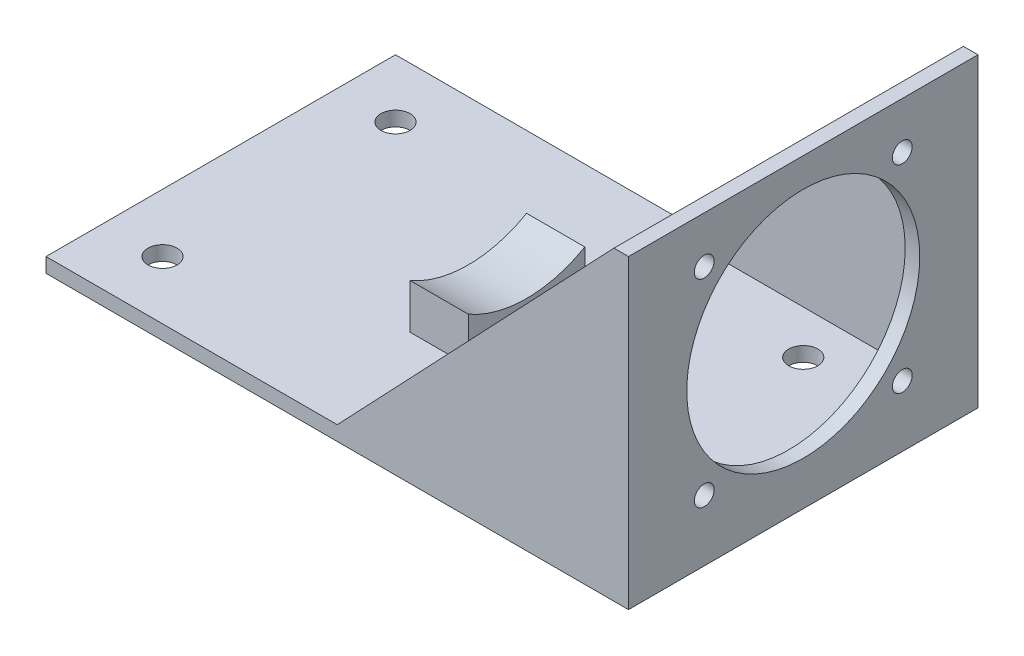
SolidWorks part; units mm, degrees
ref_plane "Front Plane" through (0, 0, 0) normal (0, 0, 1) x (1, 0, 0)
ref_plane "Top Plane" through (0, 0, 0) normal (0, 1, 0) x (1, 0, 0)
ref_plane "Right Plane" through (0, 0, 0) normal (1, 0, 0) x (0, 0, -1)
sketch "Sketch1" plane through (0, 0, 0) normal (0, 1, 0) x (1, 0, 0)
  line L1 (-127, 76.2) -> (127, 76.2)
  line L2 (-127, 76.2) -> (-127, -76.2)
  line L3 (-127, -76.2) -> (127, -76.2)
  line L4 (127, 76.2) -> (127, -76.2)
  line L5 (-127, 76.2) -> (127, -76.2) construction
  line L6 (-127, -76.2) -> (127, 76.2) construction
  point P0 (0, 0)
  dimension "D1" = 254
  dimension "D2" = 152.4
extrude "Boss-Extrude1" add sketch "Sketch1" along normal blind 6.35
sketch "Sketch2" plane through (127, 0, 0) normal (1, 0, 0) x (0, 0, -1)
  line L1 (-76.2, 6.35) -> (76.2, 6.35)
  line L2 (-76.2, 6.35) -> (-76.2, 133.35)
  line L3 (-76.2, 133.35) -> (76.2, 133.35)
  line L4 (76.2, 6.35) -> (76.2, 133.35)
  circle A0 centre (0, 69.85) radius 50.8
  circle A1 centre (-43.18, 26.67) radius 4.318
  circle A2 centre (43.18, 26.67) radius 4.318
  circle A3 centre (43.18, 113.03) radius 4.318
  circle A4 centre (-43.18, 113.03) radius 4.318
  dimension "D5" = 101.6
  dimension "D7" = 8.636
  dimension "D10" = 8.636
  dimension "D12" = 8.636
  dimension "D14" = 8.636
  dimension "D1" = 127
  dimension "D2" = 152.4
  dimension "D3" = 76.2
  dimension "D4" = 63.5
  dimension "D6" = 43.18
  dimension "D8" = 43.18
  dimension "D9" = 43.18
  dimension "D11" = 43.18
  dimension "D13" = 43.18
  dimension "D15" = 43.18
  dimension "D16" = 43.18
  dimension "D17" = 43.18
extrude "Boss-Extrude2" add sketch "Sketch2" against normal blind 6.35
sketch "Sketch3" plane through (0, 0, 76.2) normal (0, 0, 1) x (1, 0, 0)
  line L0 (120.65, 133.35) -> (0, 6.35)
  line L1 (-127, 6.35) -> (120.65, 6.35) construction
  line L2 (0, 6.35) -> (120.65, 6.35)
  line L3 (120.65, 6.35) -> (120.65, 133.35)
extrude "Boss-Extrude3" add sketch "Sketch3" against normal blind 6.35
sketch "Sketch4" plane through (0, 0, -76.2) normal (0, 0, -1) x (-1, 0, 0)
  line L0 (-120.65, 133.35) -> (0, 6.35)
  line L1 (0, 6.35) -> (-120.65, 6.35)
  line L2 (-120.65, 6.35) -> (-120.65, 133.35)
extrude "Boss-Extrude4" add sketch "Sketch4" against normal blind 6.35
sketch "Sketch5" plane through (0, 6.35, 0) normal (0, 1, 0) x (1, 0, 0)
  line L0 (120.65, -69.85) -> (120.65, 69.85) construction
  line L1 (-19.05, 25.4) -> (6.35, 25.4)
  line L2 (-19.05, 25.4) -> (-19.05, -25.4)
  line L3 (-19.05, -25.4) -> (6.35, -25.4)
  line L4 (6.35, 25.4) -> (6.35, -25.4)
  line L5 (-19.05, 25.4) -> (6.35, -25.4) construction
  line L6 (-19.05, -25.4) -> (6.35, 25.4) construction
  line L7 (0, 76.2) -> (-127, 76.2) construction
  point P0 (-6.35, 0)
  dimension "D1" = 127
  dimension "D2" = 76.2
  dimension "D3" = 50.8
  dimension "D4" = 25.4
extrude "Boss-Extrude5" add sketch "Sketch5" along normal blind 25.4
sketch "Sketch6" plane through (-19.05, 0, 0) normal (-1, 0, 0) x (0, 0, 1)
  line L0 (-76.2, 0) -> (76.2, 0) construction
  circle A0 centre (0, 69.85) radius 50.8
  dimension "D2" = 101.6
  dimension "D1" = 69.85
  dimension "D3" = 76.2
extrude "Cut-Extrude1" cut sketch "Sketch6" against normal blind 25.4
sketch "Sketch7" plane through (0, 6.35, 0) normal (0, 1, 0) x (1, 0, 0)
  line L0 (0, 76.2) -> (-127, 76.2) construction
  line L1 (127, 76.2) -> (127, -76.2) construction
  circle A0 centre (-101.6, 50.8) radius 6.35
  circle A1 centre (-101.6, -50.8) radius 6.35
  circle A2 centre (76.2, -50.8) radius 6.35
  circle A3 centre (76.2, 50.8) radius 6.35
  point P13 (0, 0)
  dimension "D3" = 12.7
  dimension "D4" = 12.7
  dimension "D5" = 12.7
  dimension "D6" = 12.7
  dimension "D1" = 25.4
  dimension "D2" = 25.4
  dimension "D7" = 101.6
  dimension "D8" = 50.8
extrude "Cut-Extrude2" cut sketch "Sketch7" against normal blind 25.4
